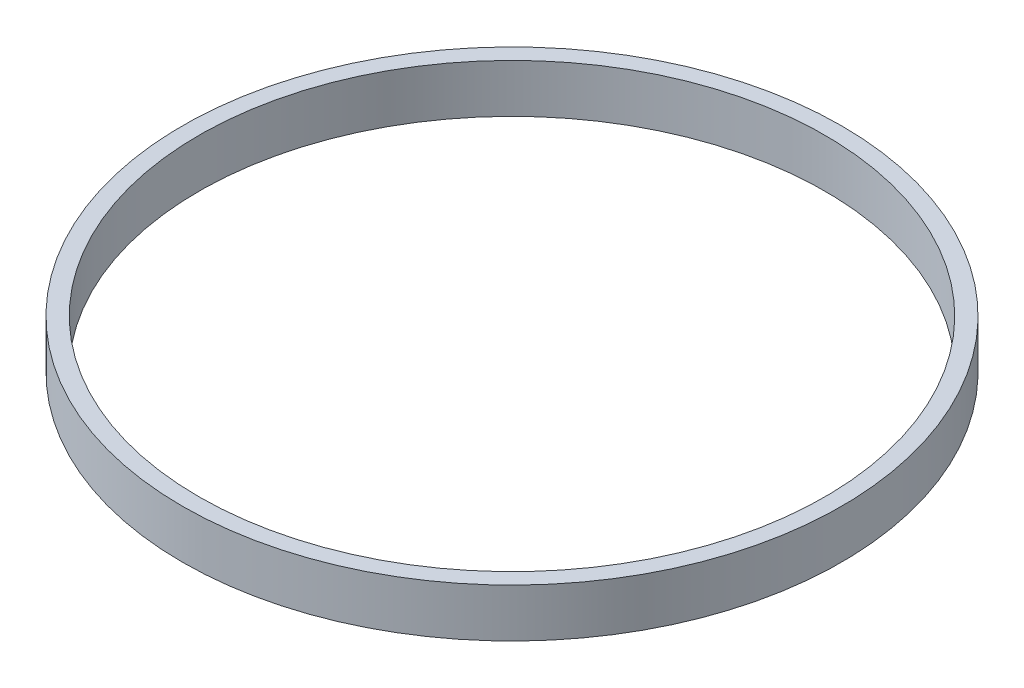
SolidWorks part; units mm, degrees
material "ABS"
ref_plane "Front Plane" through (0, 0, 0) normal (0, 0, 1) x (1, 0, 0)
ref_plane "Top Plane" through (0, 0, 0) normal (0, 1, 0) x (1, 0, 0)
ref_plane "Right Plane" through (0, 0, 0) normal (1, 0, 0) x (0, 0, -1)
sketch "Sketch1" plane through (0, 0, 0) normal (0, 1, 0) x (1, 0, 0)
  circle A0 centre (0, 0) radius 16.15
  circle A1 centre (0, 0) radius 17
  dimension "D1" = 32.3
  dimension "D2" = 34
extrude "Boss-Extrude1" add sketch "Sketch1" along normal blind 2.5 contours A1 A0
